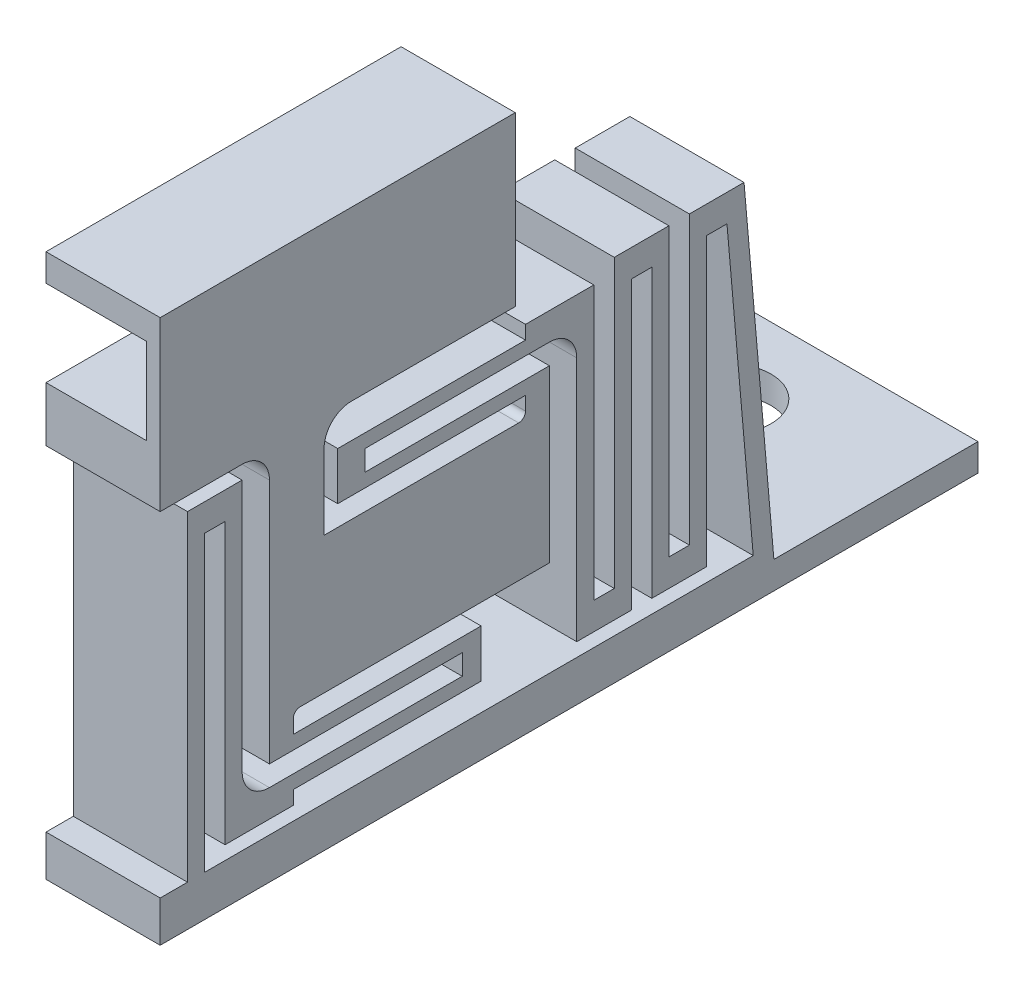
SolidWorks part; units mm, degrees
ref_plane "Front Plane" through (0, 0, 0) normal (0, 0, 1) x (1, 0, 0)
ref_plane "Top Plane" through (0, 0, 0) normal (0, 1, 0) x (1, 0, 0)
ref_plane "Right Plane" through (0, 0, 0) normal (1, 0, 0) x (0, 0, -1)
sketch "Sketch1" plane through (0, 0, 0) normal (1, 0, 0) x (0, 0, -1)
  line L0 (2.3687, -1.0669) -> (8.3687, -1.0669)
  line L1 (-4.6313, -1.0669) -> (-1.6313, -1.0669)
  line L2 (-4.6313, -1.0669) -> (-4.6313, 5.0831)
  line L3 (-4.6313, 5.0831) -> (8.3687, 5.0831)
  line L4 (8.3687, -1.0669) -> (8.3687, 5.0831)
  line L6 (-0.6313, -2.0669) -> (-0.6313, -11.0669)
  line L8 (1.3687, -2.0669) -> (1.3687, -4.8169)
  line L13 (0.4937, -9.8169) -> (9.6187, -9.8169)
  line L14 (8.7437, -4.5669) -> (8.7437, -4.0669)
  line L16 (9.6187, -9.8169) -> (9.6187, -3.5669)
  line L17 (1.8687, -2.3169) -> (1.8687, -4.0669)
  line L20 (8.7437, -4.0669) -> (1.8687, -4.0669)
  line L25 (2.8687, -3.5669) -> (2.8687, -2.8169)
  line L26 (1.8687, -2.3169) -> (8.7437, -2.3169)
  line L28 (2.8687, -2.8169) -> (9.6187, -2.8169)
  line L32 (8.7437, -2.3169) -> (8.7437, -1.8169)
  line L33 (8.7437, -1.8169) -> (11.2437, -1.8169)
  line L35 (-0.6313, -11.0669) -> (6.4278, -11.0669)
  line L36 (6.4278, -11.0669) -> (6.4278, -11.8169)
  line L37 (6.4278, -11.8169) -> (-0.6313, -11.8169)
  line L38 (13.3687, -2.3169) -> (13.3687, -12.8169)
  line L40 (-2.2563, -12.8169) -> (0.2437, -12.8169)
  line L41 (0.2437, -12.8169) -> (0.2437, -12.3169)
  line L42 (0.2437, -12.3169) -> (7.1187, -12.3169)
  line L43 (7.1187, -12.3169) -> (7.1187, -10.5669)
  line L44 (7.1187, -10.5669) -> (0.2437, -10.5669)
  line L45 (0.2437, -10.5669) -> (0.2437, -10.0669)
  line L48 (-1.6313, -10.8169) -> (-1.6313, -1.5669)
  line L50 (-2.2563, -12.8169) -> (-2.2563, -2.5669)
  line L51 (-1.6313, -1.5669) -> (-3.6313, -1.5669)
  line L53 (-2.2563, -2.5669) -> (-3.0063, -2.5669)
  line L56 (10.6187, -3.8169) -> (10.6187, -12.8169)
  line L58 (11.2437, -1.8169) -> (11.2437, -11.8169)
  line L59 (10.6187, -12.8169) -> (12.6187, -12.8169)
  line L61 (11.2437, -11.8169) -> (11.9937, -11.8169)
  line L65 (12.6187, -12.8169) -> (12.6187, -2.3169)
  line L67 (11.9937, -11.8169) -> (11.9937, -1.3169)
  line L69 (-3.6313, -1.5669) -> (-3.6313, -13.3169)
  line L71 (-3.0063, -2.5669) -> (-3.0063, -13.3169)
  line L72 (-3.6313, -13.3169) -> (-4.6313, -13.3169)
  line L75 (-4.6313, -13.3169) -> (-4.6313, -14.8169)
  line L76 (12.6187, -2.3169) -> (13.3687, -2.3169)
  line L78 (11.9937, -1.3169) -> (13.9937, -1.3169)
  line L80 (-4.6313, -14.8169) -> (17.9247, -14.8169)
  line L82 (17.081, -13.3169) -> (-3.0063, -13.3169)
  line L84 (2.8687, -3.5669) -> (9.6187, -3.5669)
  line L85 (13.3687, -12.8169) -> (15.3687, -12.8169)
  line L86 (15.3687, -12.8169) -> (15.3687, -2.3169)
  line L87 (15.3687, -2.3169) -> (16.1187, -2.3169)
  line L88 (16.1187, -2.3169) -> (17.081, -13.3169)
  line L89 (13.9937, -1.3169) -> (13.9937, -11.8169)
  line L90 (13.9937, -11.8169) -> (14.7437, -11.8169)
  line L91 (14.7437, -11.8169) -> (14.7437, -1.3169)
  line L92 (14.7437, -1.3169) -> (16.7437, -1.3169)
  line L93 (16.7437, -1.3169) -> (17.9247, -14.8169)
  line L94 (8.4937, -4.8169) -> (1.3687, -4.8169)
  line L95 (17.9247, -14.8169) -> (17.9247, -1.3169) construction
  line L96 (2.8687, -2.3169) -> (2.8687, -2.8169) construction
  line L97 (2.8687, -3.5669) -> (2.8687, -4.0669) construction
  line L98 (6.4278, -10.5669) -> (6.4278, -11.0669) construction
  line L99 (6.4278, -11.8169) -> (6.4278, -12.3169) construction
  line L100 (8.7437, -4.0669) -> (8.7437, -4.8169) construction
  line L101 (0.2437, -9.8169) -> (0.2437, -10.5669)
  line L102 (15.7437, -1.3169) -> (15.7437, -2.3169) construction
  line L103 (2.8687, -3.1919) -> (1.8687, -3.1919) construction
  line L104 (-2.6313, -1.5669) -> (-2.6313, -2.5669) construction
  line L105 (14.3687, -11.8169) -> (14.3687, -12.8169) construction
  line L106 (-3.0063, -2.5669) -> (-3.6313, -2.5669) construction
  line L107 (-2.2563, -2.5669) -> (-1.6313, -2.5669) construction
  line L108 (-2.6313, -1.0669) -> (-2.6313, -1.5669) construction
  line L109 (1.8687, -3.1919) -> (1.3687, -3.1919) construction
  line L110 (7.1187, -12.3169) -> (7.1187, -13.3169) construction
  arc A0 (2.3687, -1.0669) -> (1.3687, -2.0669) centre (2.3687, -2.0669) ccw
  arc A1 (-1.6313, -1.0669) -> (-0.6313, -2.0669) centre (-1.6313, -2.0669) cw
  arc A2 (9.6187, -2.8169) -> (10.6187, -3.8169) centre (9.6187, -3.8169) cw
  arc A3 (-0.6313, -11.8169) -> (-1.6313, -10.8169) centre (-0.6313, -10.8169) cw
  arc A4 (0.2437, -10.0669) -> (0.4937, -9.8169) centre (0.4937, -10.0669) cw
  arc A5 (8.7437, -4.5669) -> (8.4937, -4.8169) centre (8.4937, -4.5669) cw
  dimension "D4" = 1
  dimension "D14" = 0.25
  dimension "D1" = 22.5561
  dimension "D2" = 13
  dimension "D3" = 6.15
  dimension "D5" = 13.75
  dimension "D6" = 19.9
  dimension "D7" = 2
  dimension "D8" = 13.5
  dimension "D9" = 5
  dimension "D10" = 10.5
  dimension "D13" = 1.5
  dimension "D19" = 0.7098
  dimension "D25" = 6.875
  dimension "D27" = 1.75
  dimension "D32" = 10.25
  dimension "D33" = 0.875
  dimension "D35" = 1.75
  dimension "D37" = 0.5
  dimension "D39" = 2.5
  dimension "D41" = 6.875
  dimension "D42" = 0.6908
  dimension "D11" = 0.75
  dimension "D17" = 1
  dimension "D12" = 1.25
  dimension "D15" = 11.75
extrude "Flexure Boss" add sketch "Sketch1" along normal blind 4.18
sketch "Sketch2" plane through (0, -14.8169, 0) normal (0, -1, 0) x (1, 0, 0)
  line L4 (-5.32, -7.3096) -> (-5.32, -25.3096)
  line L5 (4.18, 4.6313) -> (0, 4.6313) construction
  line L7 (-5.32, -25.3096) -> (4.18, -25.3096)
  line L12 (-5.32, -7.3096) -> (4.18, -7.3096)
  line L13 (4.18, -7.3096) -> (4.18, -25.3096)
  circle A0 centre (-1.75, -10.0887) radius 1.575
  circle A1 centre (-1.75, -22.0887) radius 1.575
  dimension "D4" = 3.15
  dimension "D1" = 14.72
  dimension "D3" = 12
  dimension "MountingPlateWidth" = 9.5
  dimension "D6" = 18
  dimension "LeftEdgeDist" = 5.32
  dimension "D8" = 7.3096
  dimension "MountingHoleEdgeDist" = 3.57
extrude "Mounting Plate Boss" add sketch "Sketch2" against normal blind 1
sketch "Sketch7" plane through (0, 0, 0) normal (-1, 0, 0) x (0, 0, 1)
  line L0 (-8.3687, 0.9331) -> (4.6313, 0.9331)
  line L1 (4.6313, 4.0831) -> (4.6313, 0.9331)
  line L4 (4.6313, 4.0831) -> (-1.8687, 3.0831)
  line L5 (-1.8687, 3.0831) -> (-8.3687, 4.0831)
  line L6 (-8.3687, 4.0831) -> (-8.3687, 0.9331)
  line L7 (4.6313, -1.0669) -> (4.6313, 5.0831) construction
  line L8 (-8.3687, -1.0669) -> (-8.3687, 5.0831) construction
  point P10 (-1.8687, 0.9331)
  dimension "D1" = 2
  dimension "D2" = 2.15
  dimension "D3" = 1
extrude "Dovetail Connection Cut" cut sketch "Sketch7" against normal blind 3.68
equation "\"MountingHoleEdgeDist@Sketch2\"  = \"MountingHoleEdgeDist\""
equation "\"FlexureExtrusionThickness\"= 4.18"
equation "\"D1@Flexure Boss\"=\"FlexureExtrusionThickness\""
equation "\"MountingHoleEdgeDist\"= 3.57mm"
equation "\"FlexureGapDist\"= .75mm"
equation "\"D11@Sketch1\"=\"FlexureGapDist\""
equation "\"FlexureCornerThicknessOffset\"= .5mm"
equation "\"D37@Sketch1\"=\"FlexureCornerThicknessOffset\""
equation "\"FlexureCornerThicknessWidth\"= 2.5mm"
equation "\"D39@Sketch1\"=\"FlexureCornerThicknessWidth\""
equation "\"FlexureConnectorWidth\"= 2mm"
equation "\"FlexureConnectorThickness\"= 1mm"
equation "\"D7@Sketch1\"=\"FlexureConnectorWidth\""
equation "\"D17@Sketch1\"=\"FlexureConnectorThickness\""
equation "\"DribblerPlateHeightFromBase\"= 13.75mm"
equation "\"D5@Sketch1\"=\"DribblerPlateHeightFromBase\""
equation "\"FlexureOverallHeight\"= 13.5mm"
equation "\"D8@Sketch1\"=\"FlexureOverallHeight\""
equation "\"D15@Sketch1\"=\"DribblerPlateHeightFromBase\" - \"FlexureBaseHeight\" - \"FlexureClearanceGapDist\""
equation "\"FlexureBaseHeight\"= 1.5mm"
equation "\"D13@Sketch1\"=\"FlexureBaseHeight\""
equation "\"FlexureClearanceGapDist\"= .5mm"
